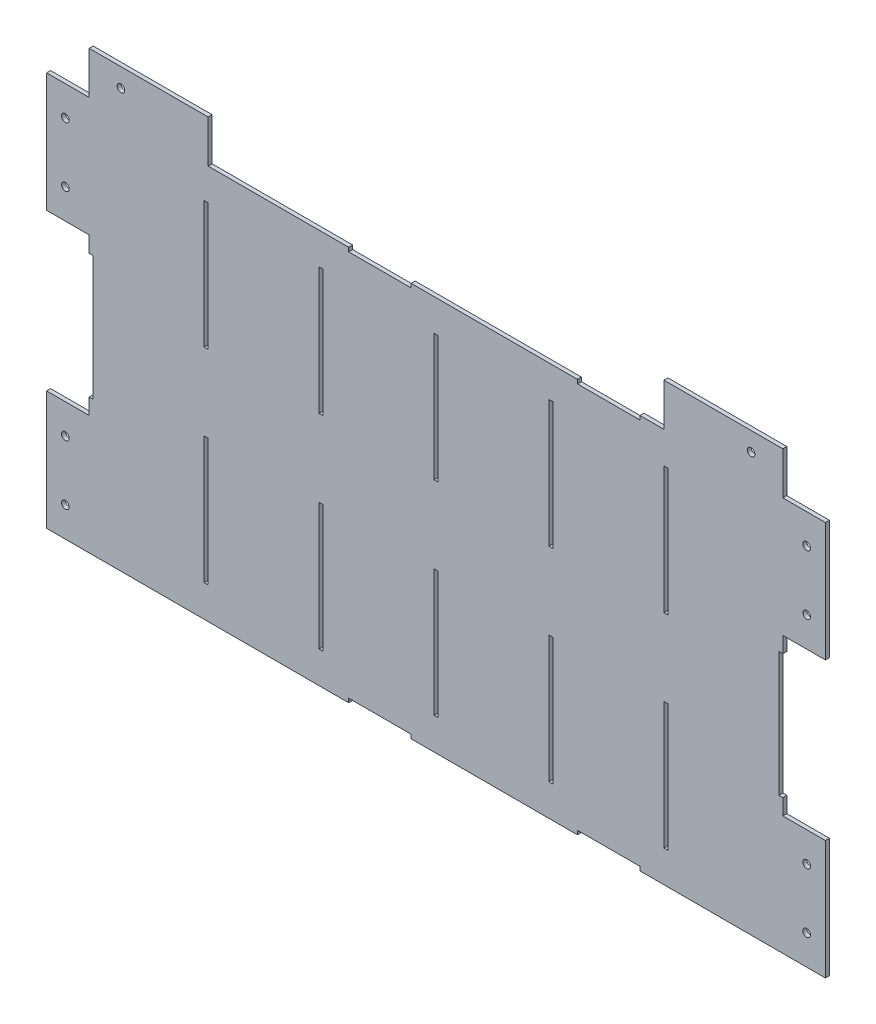
SolidWorks part; units mm, degrees
material "6061-T6 (SS)"
ref_plane "X-Y Datum" through (0, 0, 0) normal (0, 0, 1) x (1, 0, 0)
ref_plane "X-Z Datum" through (0, 0, 0) normal (0, 1, 0) x (1, 0, 0)
ref_plane "Y-Z Datum" through (0, 0, 0) normal (1, 0, 0) x (0, 0, -1)
sketch "Sketch1" plane through (0, 0, 0) normal (0, 0, 1) x (1, 0, 0)
  line L0 (-277.4525, 0) -> (277.4525, 0) construction
  line L1 (-277.4525, -157.7875) -> (277.4525, -157.7875)
  line L2 (-277.4525, -157.7875) -> (-277.4525, 157.7875)
  line L3 (-277.4525, 157.7875) -> (277.4525, 157.7875)
  line L4 (277.4525, -157.7875) -> (277.4525, 157.7875)
  line L5 (-277.4525, -157.7875) -> (277.4525, 157.7875) construction
  line L6 (-277.4525, 157.7875) -> (277.4525, -157.7875) construction
  line L7 (-274.2775, -154.615) -> (-274.2775, 154.615)
  line L8 (-272.6875, -153.025) -> (-187.0875, -153.025)
  line L9 (-272.6875, -153.025) -> (-272.6875, 153.025)
  line L10 (-272.6875, 153.025) -> (-187.0875, 153.025)
  line L11 (-187.0875, -153.025) -> (-187.0875, 153.025)
  line L12 (-272.6875, -153.025) -> (-187.0875, 153.025) construction
  line L13 (-272.6875, 153.025) -> (-187.0875, -153.025) construction
  line L14 (-274.2775, 154.615) -> (-185.4975, 154.615)
  line L15 (-185.4975, -154.615) -> (-185.4975, 154.615)
  line L16 (-274.2775, -154.615) -> (-185.4975, -154.615)
  line L17 (-182.3225, 154.615) -> (-93.5425, 154.615)
  line L18 (-180.7325, 153.025) -> (-95.1325, 153.025)
  line L19 (-182.3225, -154.615) -> (-182.3225, 154.615)
  line L20 (-180.7325, -153.025) -> (-180.7325, 153.025)
  line L21 (-93.5425, -154.615) -> (-93.5425, 154.615)
  line L22 (-95.1325, -153.025) -> (-95.1325, 153.025)
  line L23 (-180.7325, -153.025) -> (-95.1325, -153.025)
  line L24 (-182.3225, -154.615) -> (-93.5425, -154.615)
  line L25 (-180.7325, -153.025) -> (-95.1325, 153.025) construction
  line L26 (-180.7325, 153.025) -> (-95.1325, -153.025) construction
  line L27 (-90.3675, 154.615) -> (-1.5875, 154.615)
  line L28 (-88.7775, 153.025) -> (-3.1775, 153.025)
  line L29 (-90.3675, -154.615) -> (-90.3675, 154.615)
  line L30 (-88.7775, -153.025) -> (-88.7775, 153.025)
  line L31 (-1.5875, -154.615) -> (-1.5875, 154.615)
  line L32 (-3.1775, -153.025) -> (-3.1775, 153.025)
  line L33 (-88.7775, -153.025) -> (-3.1775, -153.025)
  line L34 (-90.3675, -154.615) -> (-1.5875, -154.615)
  line L35 (-88.7775, -153.025) -> (-3.1775, 153.025) construction
  line L36 (-88.7775, 153.025) -> (-3.1775, -153.025) construction
  line L37 (1.5875, 154.615) -> (90.3675, 154.615)
  line L38 (3.1775, 153.025) -> (88.7775, 153.025)
  line L39 (1.5875, -154.615) -> (1.5875, 154.615)
  line L40 (3.1775, -153.025) -> (3.1775, 153.025)
  line L41 (90.3675, -154.615) -> (90.3675, 154.615)
  line L42 (88.7775, -153.025) -> (88.7775, 153.025)
  line L43 (3.1775, -153.025) -> (88.7775, -153.025)
  line L44 (1.5875, -154.615) -> (90.3675, -154.615)
  line L45 (3.1775, -153.025) -> (88.7775, 153.025) construction
  line L46 (3.1775, 153.025) -> (88.7775, -153.025) construction
  line L47 (93.5425, 154.615) -> (182.3225, 154.615)
  line L48 (95.1325, 153.025) -> (180.7325, 153.025)
  line L49 (93.5425, -154.615) -> (93.5425, 154.615)
  line L50 (95.1325, -153.025) -> (95.1325, 153.025)
  line L51 (182.3225, -154.615) -> (182.3225, 154.615)
  line L52 (180.7325, -153.025) -> (180.7325, 153.025)
  line L53 (95.1325, -153.025) -> (180.7325, -153.025)
  line L54 (93.5425, -154.615) -> (182.3225, -154.615)
  line L55 (95.1325, -153.025) -> (180.7325, 153.025) construction
  line L56 (95.1325, 153.025) -> (180.7325, -153.025) construction
  point P0 (0, 0)
  point P8 (-229.8875, 0)
  point P17 (-137.9325, 0)
  dimension "D1" = 554.905
  dimension "D2" = 315.575
  dimension "D3" = 306.05
  dimension "D4" = 85.6
  dimension "D5" = 3.175
  dimension "D8" = 3.175
  dimension "D9" = 91.955
  dimension "D6" = 1.59
  dimension "D7" = 5
extrude "Boss-Extrude1" add sketch "Sketch1" along normal blind 3.175
sketch "Sketch2" plane through (0, 0, 3.175) normal (0, 0, 1) x (1, 0, 0)
  line L0 (-182.3225, -154.615) -> (-185.4975, -154.615) construction
  line L1 (-183.91, -154.615) -> (-183.91, 157.7875) construction
  line L2 (-277.4525, 157.7875) -> (277.4525, 157.7875) construction
  line L4 (-185.4975, -30.7875) -> (-182.3225, -30.7875)
  line L5 (-185.4975, -30.7875) -> (-185.4975, -132.3875)
  line L6 (-185.4975, -132.3875) -> (-182.3225, -132.3875)
  line L7 (-182.3225, -30.7875) -> (-182.3225, -132.3875)
  line L8 (-185.4975, -30.7875) -> (-182.3225, -132.3875) construction
  line L9 (-185.4975, -132.3875) -> (-182.3225, -30.7875) construction
  line L12 (-277.4525, -157.7875) -> (277.4525, -157.7875) construction
  point P8 (-183.91, -81.5875)
  dimension "D1" = 76.2
  dimension "D2" = 3.175
  dimension "D3" = 101.6
extrude "Cut-Extrude1" cut sketch "Sketch2" against normal blind 3.175
sketch "Sketch7" plane through (0, 0, 3.175) normal (0, 0, 1) x (1, 0, 0)
  line L0 (277.4525, -157.7875) -> (277.4525, 157.7875) construction
  line L1 (113.1525, -154.6125) -> (163.1525, -154.6125)
  line L2 (113.1525, -154.6125) -> (113.1525, -157.7875)
  line L3 (113.1525, -157.7875) -> (163.1525, -157.7875)
  line L4 (163.1525, -154.6125) -> (163.1525, -157.7875)
  line L5 (-69.8475, -154.6125) -> (-19.8475, -154.6125)
  line L6 (-69.8475, -154.6125) -> (-69.8475, -157.7875)
  line L7 (-69.8475, -157.7875) -> (-19.8475, -157.7875)
  line L8 (-19.8475, -154.6125) -> (-19.8475, -157.7875)
  dimension "D1" = 133
  dimension "D2" = 50
  dimension "D3" = 3.175
  dimension "D4" = 50
  dimension "D5" = 114.3
extrude "Cut-Extrude5" cut sketch "Sketch7" against normal blind 3.175
mirror "Mirror3" about plane through (0, 0, 0) normal (0, 1, 0) of "Cut-Extrude1"
pattern_linear "LPattern2" count 5 spacing 91.96 along (1, 0, 0) of "Mirror3", "Cut-Extrude1"
sketch "Sketch9" plane through (0, 0, 0) normal (0, 0, -1) x (-1, 0, 0)
  line L0 (-296.5025, -62.5375) -> (-296.5025, -157.7875) construction
  line L9 (-277.4525, 157.7875) -> (-182.3244, 157.7875)
  line L10 (-277.4525, 157.7875) -> (-277.4525, 191.8235)
  line L11 (-277.4525, 191.8235) -> (-182.3244, 191.8235)
  line L12 (-182.3244, 157.7875) -> (-182.3244, 191.8235)
  line L13 (-277.4525, 157.7875) -> (-315.5525, 157.7875)
  line L14 (-277.4525, 157.7875) -> (-277.4525, 62.5375)
  line L15 (-277.4525, 62.5375) -> (-315.5525, 62.5375)
  line L18 (-315.5525, 110.1625) -> (-277.4525, 110.1625) construction
  line L20 (-277.4525, -157.7875) -> (-315.5525, -157.7875)
  line L26 (-277.4525, -62.5375) -> (-315.5525, -62.5375)
  line L28 (-315.5525, -106.9875) -> (-315.5525, -157.7875) construction
  line L29 (-315.5525, -106.9875) -> (-285.4305, -106.9875) construction
  line L30 (-296.5025, -62.5375) -> (-296.5025, -110.1625) construction
  line L31 (-296.5025, -110.1625) -> (-296.5025, -157.7875) construction
  line L32 (-296.5025, -62.5375) -> (-296.5025, -110.1625) construction
  line L33 (-296.5025, -110.1625) -> (-296.5025, -157.7875) construction
  line L35 (-315.5525, 62.5375) -> (-315.5525, 157.7875) construction
  line L36 (-311.4885, 157.7875) -> (-311.4885, 62.5375)
  line L37 (-315.5525, -62.5375) -> (-315.5525, -157.7875) construction
  line L40 (-296.5025, 157.7875) -> (-296.5025, 110.1625) construction
  line L41 (-296.5025, 110.1625) -> (-296.5025, 62.5375) construction
  line L42 (-311.4885, -62.5375) -> (-311.4885, -157.7875)
  line L43 (-296.5025, 110.1625) -> (-296.5025, 62.5375) construction
  line L44 (-296.5025, -62.5375) -> (-296.5025, -110.1625) construction
  line L45 (-296.5025, -110.1625) -> (-296.5025, -157.7875) construction
  line L46 (-277.4525, -62.5375) -> (-277.4525, -157.7875)
  line L47 (-277.4525, 176.8375) -> (-182.3244, 176.8375) construction
  line L48 (-277.4525, 176.8375) -> (-252.0525, 176.8375) construction
  line L49 (-226.6525, 191.8235) -> (-226.6525, 157.7875) construction
  circle A4 centre (-296.5025, 133.975) radius 3.048
  circle A6 centre (-296.5025, 86.35) radius 3.048
  circle A7 centre (-296.5025, -86.35) radius 3.048
  circle A8 centre (-296.5025, -133.975) radius 3.048
  circle A10 centre (-252.0525, 176.8375) radius 3.048
  point P22 (-299.5505, 133.975)
  point P39 (-252.0525, 179.8855)
  dimension "D1" = 11.938
  dimension "D2" = 95.25
  dimension "D6" = 6.096
  dimension "D7" = 95.25
  dimension "D8" = 6.096
  dimension "D9" = 6.096
  dimension "D10" = 6.096
  dimension "D12" = 19.05
  dimension "D13" = 11.938
  dimension "D11" = 25.4
  dimension "D3" = 95.1281
  dimension "D4" = 34.036
  dimension "D5" = 19.05
  dimension "D14" = 25.4
extrude "Boss-Extrude3" add sketch "Sketch9" against normal blind 3.175
mirror "Mirror4" about plane through (0, 0, 0) normal (1, 0, 0) of "Boss-Extrude3"
mirror "Mirror5" about plane through (0, 0, 0) normal (0, 1, 0) of "Cut-Extrude5"
sketch "Sketch10" plane through (0, 0, 0) normal (0, 0, -1) x (-1, 0, 0)
  line L0 (-277.4525, 62.5375) -> (-277.4525, 49.8375)
  line L1 (-277.4525, -62.5375) -> (-277.4525, 62.5375) construction
  line L2 (-277.4525, -62.5375) -> (-311.4885, -62.5375) construction
  line L3 (-277.4525, 49.8375) -> (-274.2775, 49.8375)
  line L4 (-277.4525, 49.8375) -> (-277.4525, -49.8375)
  line L5 (-277.4525, -49.8375) -> (-274.2775, -49.8375)
  line L6 (-274.2775, 49.8375) -> (-274.2775, -49.8375)
  line L7 (-277.4525, 62.5375) -> (-311.4885, 62.5375) construction
  dimension "D1" = 12.7
  dimension "D2" = 3.175
  dimension "D3" = 12.7
extrude "Cut-Extrude6" cut sketch "Sketch10" against normal through all contours L6 L3 L4 L5
mirror "Mirror6" about plane through (0, 0, 0) normal (1, 0, 0) of "Cut-Extrude6"
